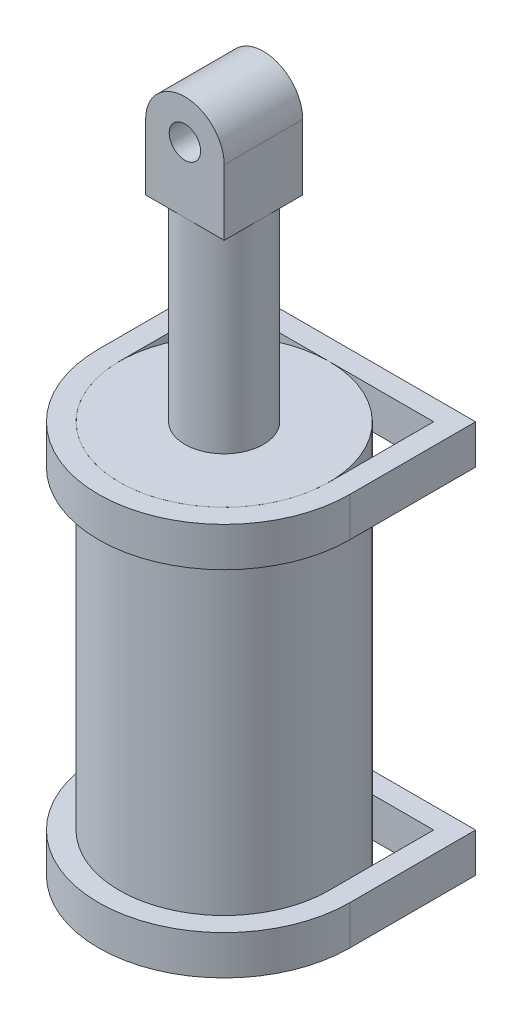
SolidWorks part; units mm, degrees
ref_plane "Front Plane" through (0, 0, 0) normal (0, 0, 1) x (1, 0, 0)
ref_plane "Top Plane" through (0, 0, 0) normal (0, 1, 0) x (1, 0, 0)
ref_plane "Right Plane" through (0, 0, 0) normal (1, 0, 0) x (0, 0, -1)
sketch "Sketch1" plane through (0, 0, 0) normal (0, 1, 0) x (1, 0, 0)
  circle A0 centre (0, 0) radius 40
  dimension "D1" = 80
extrude "Boss-Extrude1" add sketch "Sketch1" along normal mid plane 150
sketch "Sketch2" plane through (0, 75, 0) normal (0, 1, 0) x (1, 0, 0)
  circle A0 centre (0, 0) radius 15
  dimension "D1" = 30
extrude "Boss-Extrude2" add sketch "Sketch2" along normal blind 75
sketch "Sketch3" plane through (0, 150, 0) normal (0, 1, 0) x (1, 0, 0)
  line L1 (-15, 15) -> (15, 15)
  line L2 (-15, 15) -> (-15, -15)
  line L3 (-15, -15) -> (15, -15)
  line L4 (15, 15) -> (15, -15)
  line L5 (-15, 15) -> (15, -15) construction
  line L6 (-15, -15) -> (15, 15) construction
  circle A0 centre (0, 0) radius 15 construction
  point P0 (0, 0)
extrude "Boss-Extrude3" add sketch "Sketch3" along normal blind 25
sketch "Sketch4" plane through (0, 0, 15) normal (0, 0, 1) x (1, 0, 0)
  line L0 (-15, 175) -> (15, 175) construction
  line L1 (-15, 175) -> (15, 175)
  arc A0 (-15, 175) -> (15, 175) centre (0, 175) cw
extrude "Boss-Extrude4" add sketch "Sketch4" against normal up to vertex (30 mm away)
sketch "Sketch5" plane through (0, 0, 15) normal (0, 0, 1) x (1, 0, 0)
  circle A0 centre (0, 175) radius 6
  dimension "D1" = 12
extrude "Cut-Extrude1" cut sketch "Sketch5" against normal through all both and the other way through all
sketch "Sketch6" plane through (0, -75, 0) normal (0, -1, 0) x (1, 0, 0)
  line L0 (-48, 0) -> (-48, -40)
  line L1 (-48, -40) -> (-58, -40)
  line L2 (-58, -40) -> (-58, -48)
  line L3 (-58, -48) -> (0, -48)
  line L7 (48, -40) -> (48, 0)
  line L8 (-40, 0) -> (-40, -40)
  line L9 (-40, -40) -> (40, -40)
  line L10 (40, -40) -> (40, 0)
  line L11 (48, -40) -> (48, -58)
  line L12 (48, -58) -> (40, -58)
  line L13 (40, -58) -> (40, -48)
  line L14 (40, -48) -> (0, -48)
  circle A0 centre (0, 0) radius 40 construction
  arc A1 (40, 0) -> (-40, 0) centre (0, 0) ccw
  arc A2 (48, 0) -> (-48, 0) centre (0, 0) ccw
  dimension "D1" = 8
  dimension "D2" = 8
  dimension "D3" = 10
  dimension "D4" = 48
  dimension "D5" = 10
extrude "Boss-Extrude6" add sketch "Sketch6" against normal blind 15 separate body
sketch "Sketch7" plane through (0, 75, 0) normal (0, 1, 0) x (1, 0, 0)
  line L0 (40, 40) -> (40, 0) construction
  line L1 (-40, 0) -> (-40, 40) construction
  line L2 (-40, 40) -> (40, 40) construction
  line L3 (40, 40) -> (40, 0)
  line L4 (-40, 0) -> (-40, 40)
  line L5 (-40, 40) -> (40, 40)
  line L7 (48, 0) -> (48, 58)
  line L8 (40, 58) -> (40, 48)
  line L9 (48, 58) -> (40, 58)
  line L10 (40, 48) -> (-58, 48)
  line L11 (-58, 48) -> (-58, 40)
  line L12 (-58, 40) -> (-48, 40)
  line L13 (-48, 40) -> (-48, 0)
  line L14 (48, 0) -> (48, 58)
  line L16 (48, 58) -> (40, 58)
  line L17 (40, 48) -> (-58, 48)
  line L18 (-58, 48) -> (-58, 40)
  line L19 (-58, 40) -> (-48, 40)
  line L20 (-48, 40) -> (-48, 0)
  line L27 (40, 58) -> (40, 48)
  arc A0 (-40, 0) -> (40, 0) centre (0, 0) ccw construction
  arc A1 (-48, 0) -> (48, 0) centre (0, 0) ccw
  arc A2 (-48, 0) -> (48, 0) centre (0, 0) ccw
  arc A3 (-40, 0) -> (40, 0) centre (0, 0) ccw
  dimension "D1" = 0
extrude "Boss-Extrude8" add sketch "Sketch7" against normal blind 15 separate body
sketch "Sketch9" plane through (0, 0, -40) normal (0, 0, 1) x (1, 0, 0)
  line L0 (-48, -60) -> (-48, -75)
  line L1 (-48, -75) -> (-58, -75)
  line L2 (-58, -75) -> (-58, -60)
  line L3 (-58, -60) -> (-48, -60)
extrude "Cut-Extrude2" cut sketch "Sketch9" against normal blind 10
sketch "Sketch10" plane through (0, 0, -40) normal (0, 0, 1) x (1, 0, 0)
  line L0 (-48, 75) -> (-48, 60)
  line L1 (-48, 60) -> (-58, 60)
  line L2 (-58, 60) -> (-58, 75)
  line L3 (-58, 75) -> (-48, 75)
extrude "Cut-Extrude3" cut sketch "Sketch10" against normal blind 10
sketch "Sketch11" plane through (40, 0, 0) normal (-1, 0, 0) x (0, 0, 1)
  line L0 (-48, 75) -> (-58, 75)
  line L1 (-58, 75) -> (-58, 60)
  line L2 (-58, 60) -> (-48, 60)
  line L3 (-48, 60) -> (-48, 75)
extrude "Cut-Extrude4" cut sketch "Sketch11" against normal blind 10
sketch "Sketch12" plane through (40, 0, 0) normal (-1, 0, 0) x (0, 0, 1)
  line L0 (-48, -60) -> (-58, -60)
  line L1 (-48, -60) -> (-48, -75)
  line L3 (-48, -75) -> (-58, -75)
  line L4 (-58, -75) -> (-58, -60)
extrude "Cut-Extrude5" cut sketch "Sketch12" against normal blind 10
